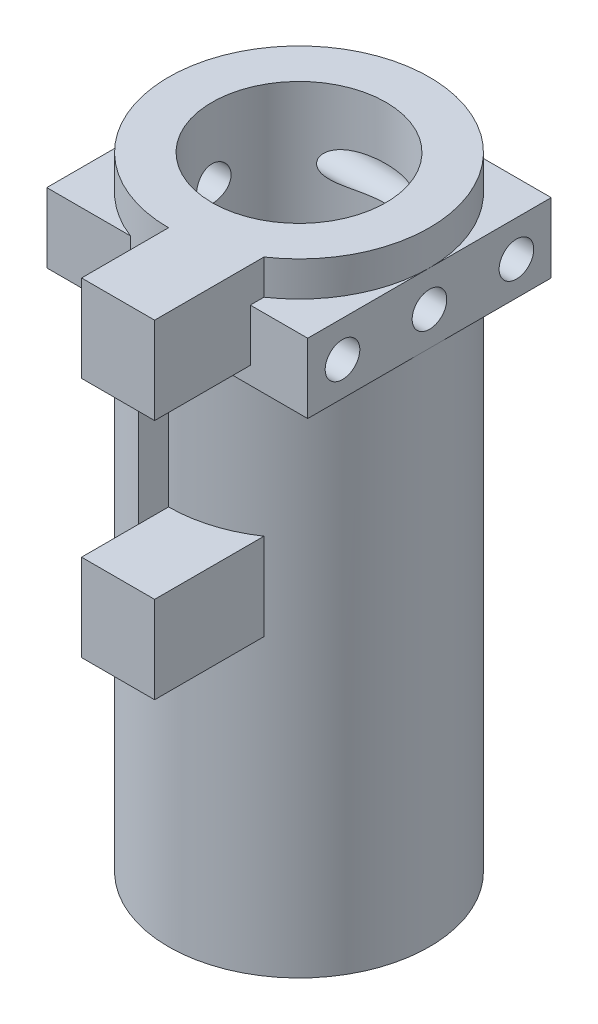
SolidWorks part; units mm, degrees
ref_plane "Front Plane" through (0, 0, 0) normal (0, 0, 1) x (1, 0, 0)
ref_plane "Top Plane" through (0, 0, 0) normal (0, 1, 0) x (1, 0, 0)
ref_plane "Right Plane" through (0, 0, 0) normal (1, 0, 0) x (0, 0, -1)
sketch "Sketch1" plane through (0, 0, 0) normal (0, 1, 0) x (1, 0, 0)
  circle A0 centre (0, 0) radius 12.7
  circle A1 centre (0, 0) radius 19.05
  dimension "D1" = 25.4
  dimension "D2" = 38.1
extrude "Boss-Extrude1" add sketch "Sketch1" against normal blind 76.2
ref_plane "Plane1" through (0, 0, 19.05) normal (0, 0, 1) x (1, 0, 0)
sketch "Sketch2" plane through (0, 0, 19.05) normal (0, 0, 1) x (1, 0, 0)
  line L0 (19.05, 0) -> (-19.05, 0) construction
  line L1 (10.668, 0) -> (0, 0)
  line L2 (10.668, 0) -> (10.668, -12.7)
  line L3 (10.668, -12.7) -> (0, -12.7)
  line L4 (0, 0) -> (0, -12.7)
  line L6 (0, -35.306) -> (10.668, -35.306)
  line L7 (0, -35.306) -> (0, -48.006)
  line L8 (0, -48.006) -> (10.668, -48.006)
  line L9 (10.668, -35.306) -> (10.668, -48.006)
  dimension "D1" = 10.668
  dimension "D2" = 12.7
  dimension "D3" = 22.606
extrude "Boss-Extrude2" add sketch "Sketch2" along normal blind 12.7 and the other way up to next
sketch "Sketch3" plane through (0, -76.2, 0) normal (0, -1, 0) x (1, 0, 0)
  circle A0 centre (0, 0) radius 19.05
extrude "Boss-Extrude3" add sketch "Sketch3" along normal blind 2.032
sketch "Sketch4" plane through (0, 0, 0) normal (0, 0, 1) x (1, 0, 0)
  line L0 (0, 0) -> (0, -12.7) construction
  line L1 (0, -6.35) -> (-5.08, -6.35)
  line L2 (0, -6.35) -> (0, -41.656)
  line L3 (0, -41.656) -> (-5.08, -41.656)
  line L4 (-5.08, -6.35) -> (-5.08, -41.656)
  line L5 (0, -35.306) -> (0, -48.006) construction
  dimension "D1" = 5.08
extrude "Cut-Extrude1" cut sketch "Sketch4" along normal through all
sketch "Sketch6" plane through (0, 0, 0) normal (0, 0, 1) x (1, 0, 0)
  line L0 (-14.478, -78.232) -> (-16.51, -90.932)
  line L1 (-16.51, -90.932) -> (-19.05, -90.932)
  line L2 (-19.05, -90.932) -> (-19.05, -78.232)
  line L3 (-19.05, -78.232) -> (-14.478, -78.232)
  line L4 (0, -78.232) -> (0, -86.9409) construction
  dimension "D1" = 14.478
  dimension "D2" = 12.7
  dimension "D3" = 2.54
revolve "Revolve2" add sketch "Sketch6" angle 360 about L4
ref_plane "Plane2" through (-19.05, 0, 0) normal (-1, 0, 0) x (0, 0, 1)
sketch "Sketch7" plane through (-19.05, 0, 0) normal (-1, 0, 0) x (0, 0, 1)
  line L0 (0, 0) -> (0, -5.08) construction
  line L1 (-17.78, -5.08) -> (17.78, -5.08)
  line L2 (-17.78, -5.08) -> (-17.78, -15.24)
  line L3 (-17.78, -15.24) -> (17.78, -15.24)
  line L4 (17.78, -5.08) -> (17.78, -15.24)
  dimension "D1" = 10.16
  dimension "D2" = 35.56
  dimension "D3" = 5.08
extrude "Boss-Extrude4" add sketch "Sketch7" against normal up to next
mirror "Mirror1" about plane through (0, 0, 0) normal (1, 0, 0) of "Boss-Extrude4"
hole_wizard "#8 (0.199) Diameter Hole1" positions "Sketch9" profile "Sketch8" hole size "#8" standard "ANSI Inch" end condition through all
sketch "Sketch9" plane through (-19.05, 0, 0) normal (-1, 0, 0) x (0, 0, 1)
  line L0 (0, 0) -> (0, -10.3128) construction
  point P0 (0, -10.3128)
  point P2 (12.7, -10.3128)
  point P4 (-12.7, -10.3128)
  dimension "D1" = 12.7
  dimension "D2" = 12.7
sketch "Sketch8" plane through (-19.05, -10.3128, 0) normal (0, 1, 0) x (0, 0, 1)
  line L0 (0, 0) -> (0, 38.1)
  line L1 (0, 38.1) -> (2.5273, 38.1)
  line L2 (2.5273, 38.1) -> (2.5273, 0)
  line L5 (2.5273, 0) -> (0, 0)
  line L11 (0, -6.35) -> (0, 107.95) construction
  dimension "Thru Hole Dia." = 5.0546
  dimension "Thru Hole Depth" = 38.1
